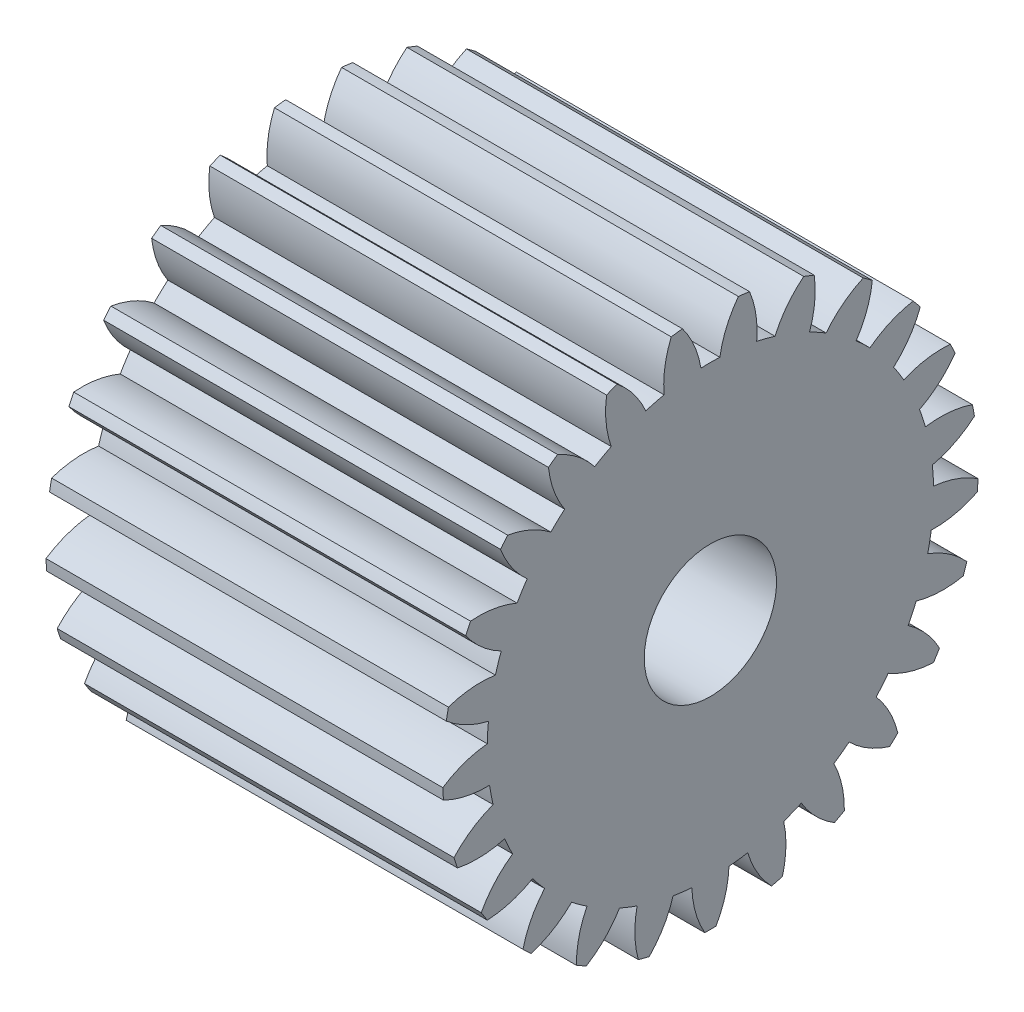
SolidWorks part; units mm, degrees
ref_plane "Plane1" through (0, 0, 0) normal (0, 0, 1) x (1, 0, 0)
ref_plane "Plane2" through (0, 0, 0) normal (0, 1, 0) x (1, 0, 0)
ref_plane "Plane3" through (0, 0, 0) normal (1, 0, 0) x (0, 0, -1)
other "Configuration Table"
sketch "HoldingSke" plane through (0, 0, 0) normal (0, 1, 0) x (1, 0, 0)
  line L0 (0, 0) -> (0.3021, -0.1409)
  line L1 (-15, 0) -> (100, 0) construction
  line L2 (0, 0) -> (-2.1039, 2.3779)
  line L3 (0, 0) -> (-11.863, 4.5341)
  line L4 (0, 0) -> (7.8269, 3.6497)
  line L5 (0, 0) -> (-46.8476, -17.4728)
  line L6 (0, 0) -> (-49.7378, -33.5582)
  line L7 (-2.1039, 2.3779) -> (10.8111, 60.9715)
  line L8 (-76.2, 54.61) -> (-73.4, 54.61)
  line L9 (-71.009, 38.7566) -> (-53.1078, 45.2721)
  line L10 (-76.2, 71.12) -> (104.1128, 71.12)
  line L11 (0, 0) -> (-60, 0)
  line L12 (-76.2, 101.6) -> (-76.093, 101.6)
  line L13 (24.9733, 27.94) -> (52.9518, 28.4284)
  line L14 (24.9733, 27.94) -> (24.9743, 27.94)
  line L15 (24.9733, 27.94) -> (100.4006, 29.5858)
  line L16 (-63.627, -3) -> (-12.827, -3)
  circle A0 centre (0, 0) radius 10
  circle A1 centre (0, 0) radius 33.749
  circle A2 centre (0, 0) radius 37.5
  circle A3 centre (0, 0) radius 10
  dimension "MHD" = 67.498
  dimension "Hub_dia" = 75
  dimension "Bore" = 20
  dimension "MBD" = 20
  dimension "Num_teeth" = 25
  dimension "Pitch" = 0.3333
  dimension "Overall_len" = 50
  dimension "Show_teeth" = 25
  dimension "Thickness" = 60
  dimension "OAL" = 60.0001
  dimension "T_dim" = 2.8
  dimension "Ap" = 20
  dimension "H" = 19.05
  dimension "Pitch_radius" = 180.3128
  dimension "Width" = 60
  dimension "Backlash" = 0.107
  dimension "Addendum_fac" = 1
  dimension "Dedendum_fac" = 1.25
  dimension "Clearance_fac" = 0.25
  dimension "Dedendum_add" = 0.001
  dimension "Module" = 3
sketch "BasProSke" plane through (0, 0, 0) normal (0, 1, 0) x (1, 0, 0)
  line L0 (-10, 0) -> (60, 0) construction
  line L1 (0, 0) -> (0, 40.5)
  line L2 (0, 0) -> (60, 0)
  line L3 (60, 0) -> (60, 40.5)
  line L4 (60, 40.5) -> (0, 40.5)
  dimension "Thickness" = 60
  dimension "Diameter" = 81
revolve "Base-Revolve" add sketch "BasProSke" angle 360 about L0
sketch "TooCutSke" plane through (0, 0, 0) normal (1, 0, 0) x (0, 0, -1)
  line L1 (0, 0) -> (0, 107) construction
  line L2 (0, 0) -> (-2.5418, 37.4138) construction
  line L3 (0, 0) -> (-9.3843, 74.2842) construction
  line L4 (-2.5418, 37.4138) -> (-4.6921, 37.1421) construction
  arc A0 (1.4296, 33.7187) -> (-1.4296, 33.7187) centre (0, 0) ccw
  arc A1 (4.2475, 40.3022) -> (-4.2475, 40.3022) centre (0, 0) ccw
  circle A2 centre (0, 0) radius 37.5 construction
  circle A3 centre (0, 0) radius 35.2385 construction
  arc A4 (-1.4296, 33.7187) -> (-4.2475, 40.3022) centre (-16.2297, 31.2785) ccw
  arc A5 (4.2475, 40.3022) -> (1.4296, 33.7187) centre (16.2297, 31.2785) ccw
  dimension "Root_dia" = 67.498
  dimension "Overcut_dia" = 81.0508
  dimension "Pitch_dia" = 75
  dimension "Base_dia" = 70.4769
  dimension "Flank_rad" = 15
  dimension "Half_ang" = 7.2
  dimension "Half_CT" = 2.1674
extrude "ToothCut" cut sketch "TooCutSke" along normal through all
fillet "Breaks" [suppressed] radius 0.06
fillet "RootFillets" [suppressed] radius 0.751
pattern_circular "TeethCuts" count 25 every 14.4 about axis through (-10, 0, 0) along (1, 0, 0) of "ToothCut", "RootFillets", "Breaks"
sketch "HubNeaOneSke" plane through (0, 0, 0) normal (-1, 0, 0) x (0, 0, 1)
  circle A0 centre (0, 0) radius 33.749
  dimension "Diameter" = 67.498
extrude "HubNearOne" [suppressed] add sketch "HubNeaOneSke" along normal blind 5.0001
sketch "HubNeaBotSke" plane through (0, 0, 0) normal (-1, 0, 0) x (0, 0, 1)
  circle A0 centre (0, 0) radius 33.749
  dimension "Diameter" = 67.498
extrude "HubNearBoth" [suppressed] add sketch "HubNeaBotSke" along normal blind 2.5
ref_plane "FarPln" through (60, 0, 0) normal (1, 0, 0) x (0, 0, -1)
sketch "HubFarSke" plane through (60, 0, 0) normal (1, 0, 0) x (0, 0, -1)
  circle A0 centre (0, 0) radius 33.749
  dimension "Diameter" = 67.498
extrude "HubFar" [suppressed] add sketch "HubFarSke" along normal blind 2.5
sketch "BorSke" plane through (0, 0, 0) normal (1, 0, 0) x (0, 0, -1)
  circle A0 centre (0, 0) radius 10
  dimension "Diameter" = 20
extrude "Bore" cut sketch "BorSke" along normal mid plane 120.0001
sketch "KeySke" plane through (0, 0, 0) normal (1, 0, 0) x (0, 0, -1)
  line L0 (-3, 0) -> (-3, 12.8)
  line L1 (-3, 12.8) -> (3, 12.8)
  line L2 (3, 12.8) -> (3, 0)
  line L3 (0, 0) -> (0, 34) construction
  line L4 (-3, 0) -> (3, 0)
  dimension "Offset" = 12.8
extrude "Keyway" [suppressed] cut sketch "KeySke" along normal mid plane 120.0001
pattern_circular "Keyway2" [suppressed] count 2 every 90 about axis through (-10, 0, 0) along (1, 0, 0)
equation "' \"Module@HoldingSke\" = 6.35"
equation "' \"Num_teeth@HoldingSke\" = 12"
equation "' \"Ap@HoldingSke\" =  20"
equation "' \"Ap@HoldingSke\" = 20"
equation "' \"Width@HoldingSke\" = 0.5 * 25.4"
equation "' \"Hub_dia@HoldingSke\"= 1 * 25.4"
equation "' \"Hub_dia@HoldingSke\" = 1 * 25.4"
equation "' \"Overall_len@HoldingSke\" = 1.0 * 25.4"
equation "' \"Bore@HoldingSke\" = 0.75 * 25.4"
equation "' \"T_dim@HoldingSke\" = 0.1 * 25.4"
equation "' \"Width@KeySke\" = 0.25 * 25.4"
equation "' \"Show_teeth@HoldingSke\" = 13"
equation "' \"Backlash@HoldingSke\" = 0.009 * 25.4"
equation "' \"Addendum_fac@HoldingSke\" = 1.0"
equation "' \"Dedendum_fac@HoldingSke\" = 1.25"
equation "' \"Dedendum_add@HoldingSke\" = 0.00005 * 25.4"
equation "' \"Clearance_fac@HoldingSke\" = 0.25"
equation "\"Pitch@HoldingSke\" = 1 / \"Module@HoldingSke\""
equation "\"Overcut_dia@TooCutSke\" = (\"Num_teeth@HoldingSke\" + 2 * \"Addendum_fac@HoldingSke\") / \"Pitch@HoldingSke\" + 0.002 * 25.4"
equation "\"Pitch_dia@TooCutSke\" = \"Num_teeth@HoldingSke\" / \"Pitch@HoldingSke\""
equation "\"Base_dia@TooCutSke\" = \"Num_teeth@HoldingSke\" / \"Pitch@HoldingSke\" * cos((\"Ap@HoldingSke\"  * 3.14159265 / 180))"
equation "\"Root_dia@TooCutSke\" = (\"Num_teeth@HoldingSke\" + 2) / \"Pitch@HoldingSke\" - 2 * (\"Addendum_fac@HoldingSke\" + \"Dedendum_fac@HoldingSke\") / \"Pitch@HoldingSke\" - \"Dedendum_add@HoldingSke\" * 2"
equation "\"Half_ang@TooCutSke\" = 180 / \"Num_teeth@HoldingSke\""
equation "\"Half_CT@TooCutSke\" = \"Num_teeth@HoldingSke\" / \"Pitch@HoldingSke\" * sin((3.14159265 / 2 / \"Num_teeth@HoldingSke\")) / 2 - 7 * \"Backlash@HoldingSke\" / 4"
equation "\"Flank_rad@TooCutSke\" = \"Num_teeth@HoldingSke\" / \"Pitch@HoldingSke\" / 5"
equation "\"Radius@RootFillets\" = \"Clearance_fac@HoldingSke\" / \"Pitch@HoldingSke\" + \"Dedendum_add@HoldingSke\""
equation "\"Break_rad@Breaks\" = 0.02 / \"Pitch@HoldingSke\""
equation "\"Thickness@HoldingSke\" = \"Width@HoldingSke\""
equation "\"OAL@HoldingSke\" = \"Thickness@HoldingSke\""
equation "\"MHD@HoldingSke\" = (\"Num_teeth@HoldingSke\" + 2) / \"Pitch@HoldingSke\" - 2 * (\"Addendum_fac@HoldingSke\" + \"Dedendum_fac@HoldingSke\")  / \"Pitch@HoldingSke\" - \"Dedendum_add@HoldingSke\" * 2"
equation "\"MBD@HoldingSke\" = (\"Num_teeth@HoldingSke\" + 2) / \"Pitch@HoldingSke\" - 2 * (\"Addendum_fac@HoldingSke\" + \"Dedendum_fac@HoldingSke\")  / \"Pitch@HoldingSke\" - \"Dedendum_add@HoldingSke\" * 2 - 0.002 * 25.4"
equation "\"MHD@HoldingSke\" = ((sgn( \"MHD@HoldingSke\" - \"Hub_dia@HoldingSke\" )-1)*( \"MHD@HoldingSke\" - \"Hub_dia@HoldingSke\" ))/-2+ \"Hub_dia@HoldingSke\""
equation "\"MBD@HoldingSke\" = ((sgn( \"MBD@HoldingSke\" - \"Bore@HoldingSke\" )-1)*( \"MBD@HoldingSke\" - \"Bore@HoldingSke\" ))/-2+ \"Bore@HoldingSke\""
equation "\"OAL@HoldingSke\" = ((sgn( \"OAL@HoldingSke\" - \"Overall_len@HoldingSke\" )+1)*( \"OAL@HoldingSke\" - \"Overall_len@HoldingSke\" ))/2 + \"Overall_len@HoldingSke\" + 0.000002 * 25.4"
equation "\"Num_teeth@TeethCuts\" = int( \"Show_teeth@HoldingSke\" ) + 1"
equation "\"Num_teeth@TeethCuts\" = ((sgn( \"Num_teeth@TeethCuts\" - \"Num_teeth@HoldingSke\" )-1)*( \"Num_teeth@TeethCuts\" - \"Num_teeth@HoldingSke\" ))/-2+ \"Num_teeth@HoldingSke\""
equation "\"Num_teeth@TeethCuts\" = ((sgn( \"Num_teeth@TeethCuts\" - 2.0)+1)*( \"Num_teeth@TeethCuts\" - 2.0))/2 +2.0"
equation "\"Angle@TeethCuts\" = 360.0 / \"Num_teeth@HoldingSke\""
equation "\"Diameter@BasProSke\" = (\"Num_teeth@HoldingSke\" + 2 * \"Addendum_fac@HoldingSke\") / \"Pitch@HoldingSke\""
equation "\"Thickness@BasProSke\"  = \"Thickness@HoldingSke\""
equation "' \"Fillet_rad@BasProSke\" =  \"Thickness@HoldingSke\" * 0.05"
equation "' \"Fillet_rad@BasProSke\" = \"Thickness@HoldingSke\" * 0.05"
equation "\"MHD@HoldingSke\" = ((sgn( \"MHD@HoldingSke\" - \"Root_dia@TooCutSke\" )-1)*( \"MHD@HoldingSke\" - \"Root_dia@TooCutSke\" ))/-2+ \"Root_dia@TooCutSke\""
equation "\"Diameter@HubNeaOneSke\" = \"MHD@HoldingSke\""
equation "\"Length@HubNearOne\" = \"OAL@HoldingSke\" - \"Thickness@BasProSke\""
equation "\"Diameter@HubNeaBotSke\" = \"MHD@HoldingSke\""
equation "\"Length@HubNearBoth\" = ( \"OAL@HoldingSke\" - \"Thickness@BasProSke\" ) / 2.0"
equation "\"Thickness@FarPln\" = \"Thickness@BasProSke\""
equation "\"Diameter@HubFarSke\" = \"MHD@HoldingSke\""
equation "\"Length@HubFar\" = ( \"OAL@HoldingSke\" - \"Thickness@BasProSke\" ) / 2.0"
equation "\"Diameter@BorSke\" = \"MBD@HoldingSke\""
equation "\"D1@Bore\" = \"OAL@HoldingSke\" * 2.0"
equation "\"D1@Keyway\" = \"OAL@HoldingSke\" * 2.0"
equation "\"Offset@KeySke\" = \"T_dim@HoldingSke\" + \"MBD@HoldingSke\" / 2.0"
